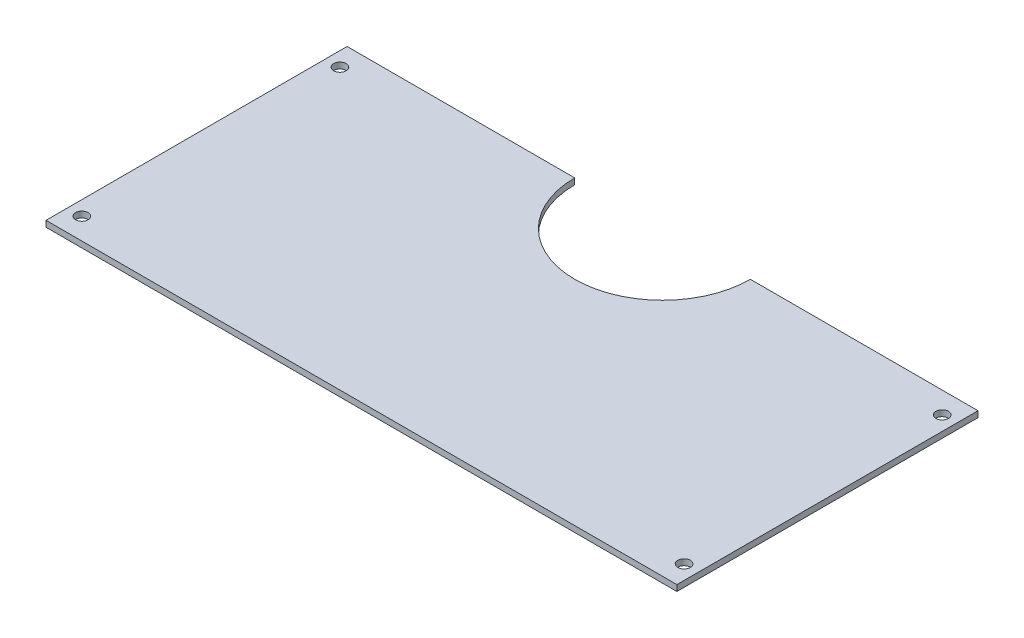
SolidWorks part; units mm, degrees
ref_plane "Front Plane" through (0, 0, 0) normal (0, 0, 1) x (1, 0, 0)
ref_plane "Top Plane" through (0, 0, 0) normal (0, 1, 0) x (1, 0, 0)
ref_plane "Right Plane" through (0, 0, 0) normal (1, 0, 0) x (0, 0, -1)
sketch "Sketch1" plane through (0, 0, 0) normal (0, 1, 0) x (1, 0, 0)
  line L1 (-139.7, -66.675) -> (139.7, -66.675)
  line L2 (-139.7, -66.675) -> (-139.7, 66.675)
  line L3 (-139.7, 66.675) -> (139.7, 66.675)
  line L4 (139.7, -66.675) -> (139.7, 66.675)
  line L5 (-139.7, -66.675) -> (139.7, 66.675) construction
  line L6 (-139.7, 66.675) -> (139.7, -66.675) construction
  point P0 (0, 0)
  dimension "D1" = 139.7
  dimension "D2" = 66.675
extrude "Boss-Extrude1" add sketch "Sketch1" along normal mid plane 2.667
sketch "Sketch2" plane through (0, 0, 0) normal (0, 1, 0) x (1, 0, 0)
  circle A0 centre (0, 66.675) radius 38.8874
  point P2 (0, 0)
  dimension "D1" = 77.7748
  dimension "D2" = 66.675
extrude "Cut-Extrude2" cut sketch "Sketch2" against normal through all from offset 1.3335
sketch "Sketch3" plane through (0, 0, 0) normal (0, 1, 0) x (1, 0, 0)
  circle A0 centre (-133.35, -57.15) radius 2.7686
  circle A1 centre (133.35, -57.15) radius 2.7686
  circle A2 centre (-133.35, 57.15) radius 2.7686
  circle A3 centre (133.35, 57.15) radius 2.7686
  point P8 (0, 0)
  dimension "D1" = 5.5372
  dimension "D2" = 5.5372
  dimension "D3" = 5.5372
  dimension "D4" = 5.5372
  dimension "D5" = 266.7
  dimension "D6" = 114.3
  dimension "D7" = 133.35
  dimension "D8" = 57.15
extrude "Cut-Extrude4" cut sketch "Sketch3" against normal through all from offset 1.3335
